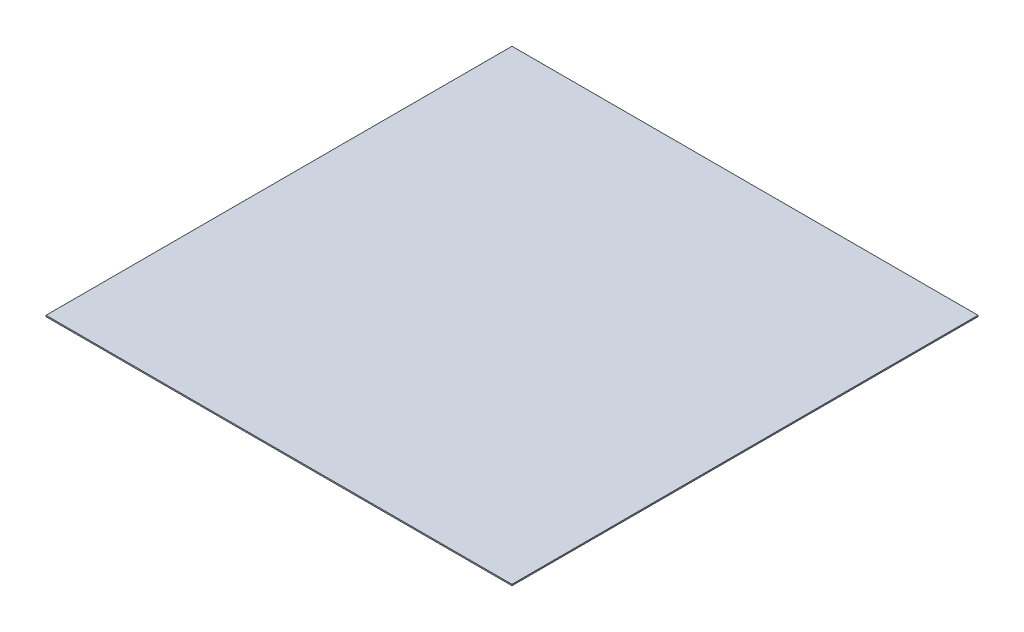
SolidWorks part; units mm, degrees
material "Maple"
ref_plane "Front Plane" through (0, 0, 0) normal (0, 0, 1) x (1, 0, 0)
ref_plane "Top Plane" through (0, 0, 0) normal (0, 1, 0) x (1, 0, 0)
ref_plane "Right Plane" through (0, 0, 0) normal (1, 0, 0) x (0, 0, -1)
sketch "Sketch1" plane through (0, 0, 0) normal (0, 1, 0) x (1, 0, 0)
  line L1 (-1828.8, 1828.8) -> (1828.8, 1828.8)
  line L2 (-1828.8, 1828.8) -> (-1828.8, -1828.8)
  line L3 (-1828.8, -1828.8) -> (1828.8, -1828.8)
  line L4 (1828.8, 1828.8) -> (1828.8, -1828.8)
  line L5 (-1828.8, 1828.8) -> (1828.8, -1828.8) construction
  line L6 (-1828.8, -1828.8) -> (1828.8, 1828.8) construction
  point P0 (0, 0)
  dimension "D1" = 3657.6
  dimension "D2" = 3657.6
extrude "Boss-Extrude1" add sketch "Sketch1" along normal blind 10
